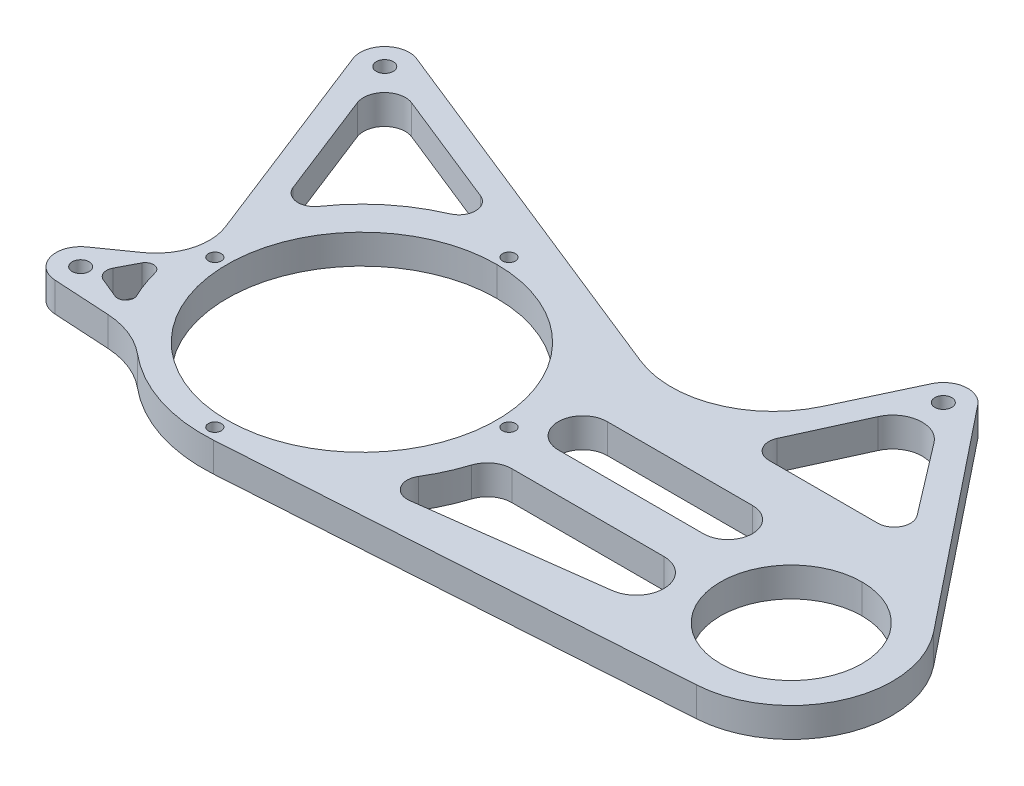
SolidWorks part; units mm, degrees
material "7075-T6 (SN)"
ref_plane "X-Y Datum" through (0, 0, 0) normal (0, 0, 1) x (1, 0, 0)
ref_plane "X-Z Datum" through (0, 0, 0) normal (0, 1, 0) x (1, 0, 0)
ref_plane "Y-Z Datum" through (0, 0, 0) normal (1, 0, 0) x (0, 0, -1)
sketch "Sketch1" plane through (0, 0, 0) normal (0, 1, 0) x (1, 0, 0)
  line L1 (0, 0) -> (54.61, -127) construction
  line L2 (-123.19, -116.0015) -> (54.61, -127) construction
  line L3 (-228.6, -146.8882) -> (-228.6, 0) construction
  line L4 (-116.84, 0) -> (0, 0) construction
  line L5 (-228.6, 0) -> (-116.84, 0) construction
  line L10 (-228.6, 0) -> (-123.19, -116.0015) construction
  line L11 (-123.19, -116.0015) -> (10.0337, -23.3342) construction
  line L15 (-207.9749, -9.9568) -> (-62.7807, -68.145)
  line L16 (-119.1621, -177.7828) -> (57.1713, -166.2866)
  line L17 (17.4773, -17.3912) -> (85.3768, -102.4358)
  line L18 (1.4126, -19.2843) -> (-12.1766, -48.2122)
  line L21 (-220.3888, -22.2676) -> (-188.53, -103.7238)
  line L23 (-228.6, -146.8882) -> (-123.19, -116.0015) construction
  line L24 (-203.8085, -154.7138) -> (-181.9442, -155.9846)
  line L25 (-208.7451, -137.4207) -> (-195.9422, -128.3923)
  circle A0 centre (-211.5182, -18.7982) radius 9.525 construction
  circle A2 centre (10.0337, -23.3342) radius 9.525 construction
  circle A3 centre (-211.5182, -18.7982) radius 3.3 construction
  circle A4 centre (-203.2558, -145.2049) radius 3.3 construction
  circle A5 centre (-123.19, -116.0015) radius 52.3875
  circle A6 centre (54.61, -127) radius 27.5
  circle A7 centre (0, 0) radius 12.7 construction
  circle A8 centre (-228.6, -146.8882) radius 12.7 construction
  circle A9 centre (-228.6, 0) radius 12.7 construction
  circle A10 centre (10.0337, -23.3342) radius 3.3 construction
  circle A11 centre (-123.19, -173.1515) radius 2.5 construction
  circle A14 centre (-123.19, -116.0015) radius 61.9125 construction
  circle A15 centre (-123.19, -116.0015) radius 57.15 construction
  circle A17 centre (-203.2558, -145.2049) radius 9.525 construction
  circle A18 centre (54.61, -127) radius 39.37 construction
  circle A19 centre (-48.0406, -31.3647) radius 39.624 construction
  arc A20 (-12.1766, -48.2122) -> (-62.7807, -68.145) centre (-48.0406, -31.3647) cw
  arc A24 (57.1713, -166.2866) -> (85.3768, -102.4358) centre (54.61, -127) ccw
  arc A25 (1.4126, -19.2843) -> (17.4773, -17.3912) centre (10.0337, -23.3342) cw
  arc A30 (-220.3888, -22.2676) -> (-207.9749, -9.9568) centre (-211.5182, -18.7982) cw
  arc A31 (-162.8594, -163.5356) -> (-119.1621, -177.7828) centre (-123.19, -116.0015) ccw
  circle A35 centre (-207.9749, -111.329) radius 20.8792 construction
  circle A36 centre (-183.8446, -188.6813) radius 32.7518 construction
  arc A37 (-208.7451, -137.4207) -> (-203.8085, -154.7138) centre (-203.2558, -145.2049) ccw
  arc A38 (-181.9442, -155.9846) -> (-162.8594, -163.5356) centre (-183.8446, -188.6813) cw
  arc A39 (-195.9422, -128.3923) -> (-188.53, -103.7238) centre (-207.9749, -111.329) ccw
  point P36 (-123.19, -116.0015)
  dimension "D1" = 146.8882
  dimension "D2" = 105.41
  dimension "D8" = 25.4
  dimension "D9" = 104.775
  dimension "D10" = 55
  dimension "D11" = 19.05
  dimension "D12" = 6.6
  dimension "D23" = 5
  dimension "D14" = 123.825
  dimension "D19" = 79.248
  dimension "D20" = 31.3647
  dimension "D16" = 78.74
  dimension "D25" = 60.6546
  dimension "D21" = 20.9
  dimension "D26" = 65.5036
  dimension "D22" = 24.7915
  dimension "D27" = 41.7585
  dimension "D3" = 111.76
  dimension "D4" = 228.6
  dimension "D5" = 127
  dimension "D6" = 25.4
  dimension "D7" = 283.21
  dimension "D13" = 25.4
  dimension "D15" = 30.8867
  dimension "D17" = 25.4
  dimension "D18" = 48.0406
  dimension "D24" = 57.15
  dimension "D28" = 84.7849
extrude "Boss-Extrude1" add sketch "Sketch1" along normal blind 11.43
hole_wizard "M6 Clearance Hole1" positions "Sketch2" profile "Sketch3" hole size "M6" standard "ANSI Metric" end condition through all
sketch "Sketch2" plane through (0, 0, 0) normal (0, -1, 0) x (-1, 0, 0)
  point P0 (-10.0337, -23.3342)
  point P3 (211.5182, -18.7982)
  point P6 (203.2558, -145.2049)
sketch "Sketch3" plane through (10.0337, 0, 23.3342) normal (1, 0, 0) x (0, 0, -1)
  line L0 (0, 0) -> (0, 11.43)
  line L1 (0, 11.43) -> (3.3, 11.43)
  line L2 (3.3, 11.43) -> (3.3, 0)
  line L5 (3.3, 0) -> (0, 0)
  line L11 (0, -6.35) -> (0, 107.95) construction
  dimension "Thru Hole Dia." = 6.6
  dimension "Thru Hole Depth" = 11.43
hole_wizard "Ø5.0mm Dowel Hole1" positions "Sketch4" profile "Sketch5" hole size "Ø5.0" standard "ANSI Metric" end condition through all
sketch "Sketch4" plane through (0, 0, 0) normal (0, -1, 0) x (-1, 0, 0)
  point P0 (123.19, -173.1515)
sketch "Sketch5" plane through (-123.19, 0, 173.1515) normal (1, 0, 0) x (0, 0, -1)
  line L0 (0, 0) -> (0, 11.43)
  line L1 (0, 11.43) -> (2.5, 11.43)
  line L2 (2.5, 11.43) -> (2.5, 0)
  line L5 (2.5, 0) -> (0, 0)
  line L11 (0, -6.35) -> (0, 107.95) construction
  dimension "Thru Hole Dia." = 5
  dimension "Thru Hole Depth" = 11.43
pattern_circular "CirPattern1" count 4 over 360 about axis through (-123.19, 0, 116.0015) along (0, 1, 0) of "Ø5.0mm Dowel Hole1"
ref_point "Point1"
ref_point "Point2"
ref_plane "Plane1" through (-123.19, 0, 0) normal (1, 0, 0) x (0, 0, -1)
ref_plane "Plane2" through (54.61, 0, 0) normal (1, 0, 0) x (0, 0, -1)
split line "Split Line1"
split line "Split Line2"
sketch "Sketch6" plane through (0, 0, 0) normal (0, -1, 0) x (1, 0, 0)
  line L0 (-10.1828, 67.6907) -> (2.0865, 40.7709)
  line L1 (21.6652, 38.5626) -> (42.9808, 66.4698)
  line L2 (-204.6607, 36.3314) -> (-188.6269, 77.3262)
  line L3 (-194.0427, 25.8017) -> (-149.3861, 43.6983)
  line L5 (-4.4047, 76.6742) -> (37.9345, 76.6742)
  line L8 (-220.3888, 22.2676) -> (-188.53, 103.7238) construction
  line L9 (17.4773, 17.3912) -> (85.3768, 102.4358) construction
  line L10 (1.4126, 19.2843) -> (-12.1766, 48.2122) construction
  line L11 (-207.9749, 9.9568) -> (-62.7807, 68.145) construction
  line L19 (-203.2558, 145.2049) -> (-184.9336, 138.522) construction
  line L21 (-194.3723, 145.2694) -> (-186.6889, 148.4277)
  line L22 (-196.5, 139.436) -> (-192.6543, 132.0726)
  circle A0 centre (10.0337, 23.3342) radius 3.3 construction
  circle A1 centre (10.0337, 23.3342) radius 3.3 construction
  arc A2 (54.61, 99.5) -> (54.61, 154.5) centre (54.61, 127) ccw construction
  circle A3 centre (-4.4047, 70.3242) radius 6.35 construction
  circle A4 centre (37.9345, 70.3242) radius 6.35 construction
  circle A5 centre (12.5377, 45.5343) radius 11.4855 construction
  arc A6 (2.0865, 40.7709) -> (21.6652, 38.5626) centre (12.5377, 45.5343) ccw
  arc A8 (42.9808, 66.4698) -> (37.9345, 76.6742) centre (37.9345, 70.3242) ccw
  arc A9 (-10.1828, 67.6907) -> (-4.4047, 76.6742) centre (-4.4047, 70.3242) cw
  circle A10 centre (-182.5949, 74.967) radius 6.477 construction
  circle A11 centre (-151.7955, 49.7105) radius 6.477 construction
  circle A14 centre (-197.0734, 33.3639) radius 8.1469 construction
  arc A15 (-204.6607, 36.3314) -> (-194.0427, 25.8017) centre (-197.0734, 33.3639) ccw
  circle A24 centre (-185.477, 145.4794) radius 3.1877 construction
  arc A25 (-149.3861, 43.6983) -> (-149.2293, 55.6575) centre (-151.7955, 49.7105) ccw
  circle A26 centre (-123.19, 116.0015) radius 65.7225
  circle A27 centre (-123.19, 116.0015) radius 65.7225 construction
  arc A28 (-149.2293, 55.6575) -> (-177.2657, 78.6482) centre (-123.19, 116.0015) cw
  arc A29 (-188.6269, 77.3262) -> (-177.2657, 78.6482) centre (-182.5949, 74.967) cw
  circle A38 centre (-189.8288, 133.5482) radius 3.1877 construction
  circle A39 centre (-192.7742, 141.3818) radius 4.2032 construction
  arc A40 (-186.7462, 132.7366) -> (-182.5957, 144.1158) centre (-123.19, 116.0015) cw
  arc A41 (-196.5, 139.436) -> (-194.3723, 145.2694) centre (-192.7742, 141.3818) cw
  arc A42 (-186.6889, 148.4277) -> (-182.5957, 144.1158) centre (-185.477, 145.4794) cw
  arc A43 (-192.6543, 132.0726) -> (-186.7462, 132.7366) centre (-189.8288, 133.5482) ccw
  dimension "D3" = 12.7
  dimension "D4" = 22.2001
  dimension "D5" = 12.954
  dimension "D9" = 6.3754
  dimension "D10" = 6.35
  dimension "D12" = 8.4065
  dimension "D1" = 358.769
  dimension "D2" = 0.66
  dimension "D6" = 46.99
  dimension "D7" = 14.4448
  dimension "D8" = 3.81
  dimension "D11" = 11.1571
extrude "Cut-Extrude1" cut sketch "Sketch6" against normal through all
sketch "Sketch7" plane through (0, 0, 0) normal (0, -1, 0) x (1, 0, 0)
  line L0 (-48.8157, 114.0965) -> (7.5723, 114.0965)
  line L1 (-48.8157, 95.0465) -> (7.5723, 95.0465)
  line L4 (-60.7098, 160.0148) -> (8.9698, 150.9177)
  line L6 (-51.5252, 129.4185) -> (7.5723, 129.4185)
  line L7 (-123.19, 116.0015) -> (54.61, 127) construction
  circle A0 centre (-48.8157, 104.5715) radius 9.525 construction
  circle A3 centre (7.5723, 104.5715) radius 9.525 construction
  arc A4 (-48.8157, 95.0465) -> (-48.8157, 114.0965) centre (-48.8157, 104.5715) cw
  arc A5 (7.5723, 95.0465) -> (7.5723, 114.0965) centre (7.5723, 104.5715) ccw
  circle A12 centre (-51.5252, 138.9435) radius 9.525 construction
  circle A14 centre (-61.5483, 153.5923) radius 6.477 construction
  arc A15 (-60.5967, 136.0394) -> (-67.0782, 150.2201) centre (-123.19, 116.0015) ccw
  arc A16 (-67.0782, 150.2201) -> (-60.7098, 160.0148) centre (-61.5483, 153.5923) cw
  arc A17 (-60.5967, 136.0394) -> (-51.5252, 129.4185) centre (-51.5252, 138.9435) ccw
  circle A19 centre (7.5723, 140.2135) radius 10.795 construction
  arc A20 (8.9698, 150.9177) -> (7.5723, 129.4185) centre (7.5723, 140.2135) cw
  circle A28 centre (-123.19, 116.0015) radius 65.7225
  circle A29 centre (-123.19, 116.0015) radius 65.7225 construction
  dimension "D1" = 19.05
  dimension "D2" = 11.43
  dimension "D5" = 12.954
  dimension "D8" = 35.642
  dimension "D3" = 21.59
  dimension "D4" = 56.388
  dimension "D7" = 33.7133
  dimension "D6" = 3.81
extrude "Cut-Extrude2" cut sketch "Sketch7" against normal through all
sketch "Sketch8" [suppressed] plane through (0, 0, 0) normal (0, -1, 0) x (1, 0, 0)
  line L0 (21.6652, 38.5626) -> (42.9808, 66.4698) construction
  line L1 (-10.1828, 67.6907) -> (2.0865, 40.7709) construction
  line L2 (37.9345, 76.6742) -> (-4.4047, 76.6742) construction
  line L3 (21.6652, 38.5626) -> (42.9808, 66.4698)
  line L4 (-10.1828, 67.6907) -> (2.0865, 40.7709)
  line L5 (37.9345, 76.6742) -> (-4.4047, 76.6742)
  arc A0 (42.9808, 66.4698) -> (37.9345, 76.6742) centre (37.9345, 70.3242) ccw construction
  arc A1 (2.0865, 40.7709) -> (21.6652, 38.5626) centre (12.5377, 45.5343) ccw construction
  arc A2 (-4.4047, 76.6742) -> (-10.1828, 67.6907) centre (-4.4047, 70.3242) ccw construction
  arc A3 (42.9808, 66.4698) -> (37.9345, 76.6742) centre (37.9345, 70.3242) ccw
  arc A4 (2.0865, 40.7709) -> (21.6652, 38.5626) centre (12.5377, 45.5343) ccw
  arc A5 (-4.4047, 76.6742) -> (-10.1828, 67.6907) centre (-4.4047, 70.3242) ccw
extrude "Boss-Extrude3" [suppressed] add sketch "Sketch8" against normal blind 11.43
